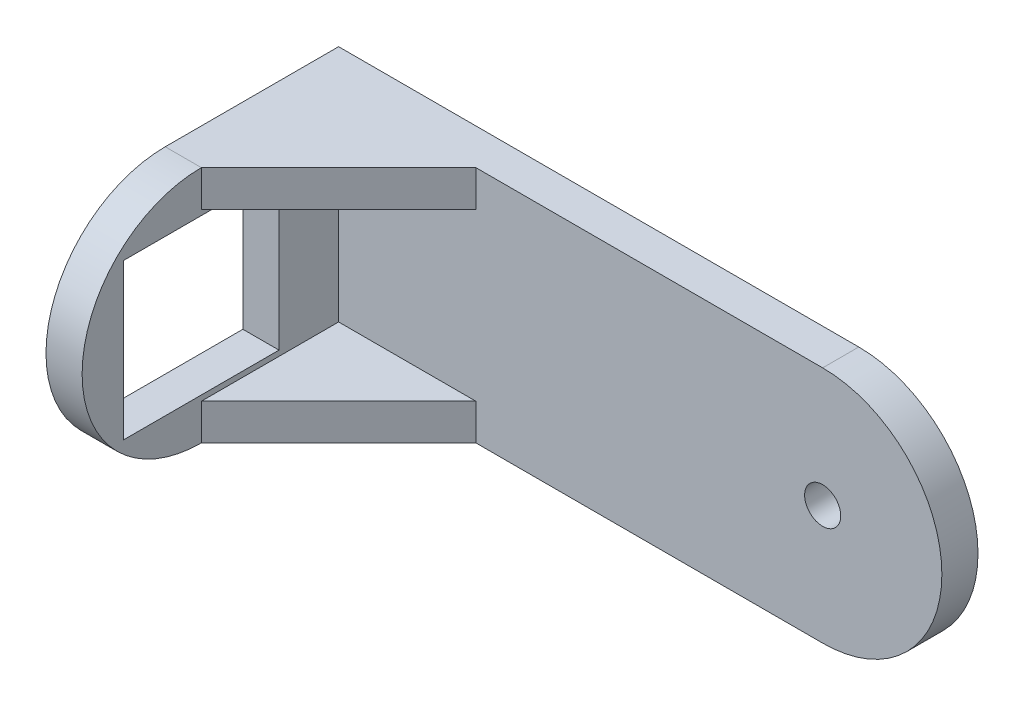
SolidWorks part; units mm, degrees
ref_plane "Front Plane" through (0, 0, 0) normal (0, 0, 1) x (1, 0, 0)
ref_plane "Top Plane" through (0, 0, 0) normal (0, 1, 0) x (1, 0, 0)
ref_plane "Right Plane" through (0, 0, 0) normal (1, 0, 0) x (0, 0, -1)
sketch "Sketch1" plane through (0, 0, 0) normal (0, 0, 1) x (1, 0, 0)
  line L0 (123.1491, -410.7524) -> (122.8965, 248.2476) construction
  line L1 (0, 33) -> (-144, 33)
  line L2 (-144, 33) -> (-144, -33)
  line L3 (-144, -33) -> (0, -33)
  arc A0 (0, 33) -> (0, -33) centre (0, 0) cw
  circle A1 centre (0, 0) radius 5
  dimension "D2" = 33
  dimension "D5" = 10
  dimension "D1" = 659
  dimension "D3" = 144
  dimension "D4" = 66
extrude "Boss-Extrude1" add sketch "Sketch1" along normal blind 10
sketch "Sketch3" plane through (-144, 0, 0) normal (-1, 0, 0) x (0, 0, 1)
  line L0 (0, 33) -> (0, -33) construction
  line L1 (0, 33) -> (48, 33)
  line L2 (0, 33) -> (0, -33)
  line L3 (0, -33) -> (48, -33)
  line L5 (26.5, 21.5) -> (69.5, -21.5) construction
  line L6 (26.5, 21.5) -> (69.5, 21.5)
  line L7 (26.5, 21.5) -> (26.5, -21.5)
  line L8 (26.5, -21.5) -> (69.5, -21.5)
  line L9 (69.5, 21.5) -> (69.5, -21.5)
  line L10 (69.5, 21.5) -> (26.5, -21.5) construction
  line L11 (10, -33) -> (0, -33) construction
  line L12 (10, 33) -> (10, -33)
  line L13 (10, 33) -> (10, -33) construction
  arc A0 (48, 33) -> (48, -33) centre (48, 0) cw
  point P10 (48, 21.5)
  point P12 (26.5, 0)
  line M9 (10, -33) -> (10, 33)
  dimension "D1" = 48
  dimension "D2" = 43
extrude "Boss-Extrude3" add sketch "Sketch3" against normal blind 10 contours A0 L1 L3 L6 L9 L8 L7 M9
sketch "Sketch4" plane through (0, 33, 0) normal (0, 1, 0) x (1, 0, 0)
  line L0 (-134, -48) -> (-96, -10)
  line L1 (-134, -10) -> (-134, -48) construction
  line L2 (0, -10) -> (-134, -10) construction
  line L3 (-134, -48) -> (-134, -10)
  line L4 (-134, -10) -> (-96, -10)
  dimension "D1" = 45
extrude "Boss-Extrude4" add sketch "Sketch4" against normal blind 10
ref_plane "Plane1" through (0, 0, 0) normal (0, 1, 0) x (1, 0, 0)
mirror "Mirror1" about plane through (0, 0, 0) normal (0, 1, 0) of "Boss-Extrude4"
equation "\"Thicknes\"=20"
equation "\"D1@Boss-Extrude1\"=\"Thicknes\"/2"
equation "\"D1@Boss-Extrude3\"=\"Thicknes\"/2"
equation "\"D1@Boss-Extrude4\"=\"Thicknes\"/2"
